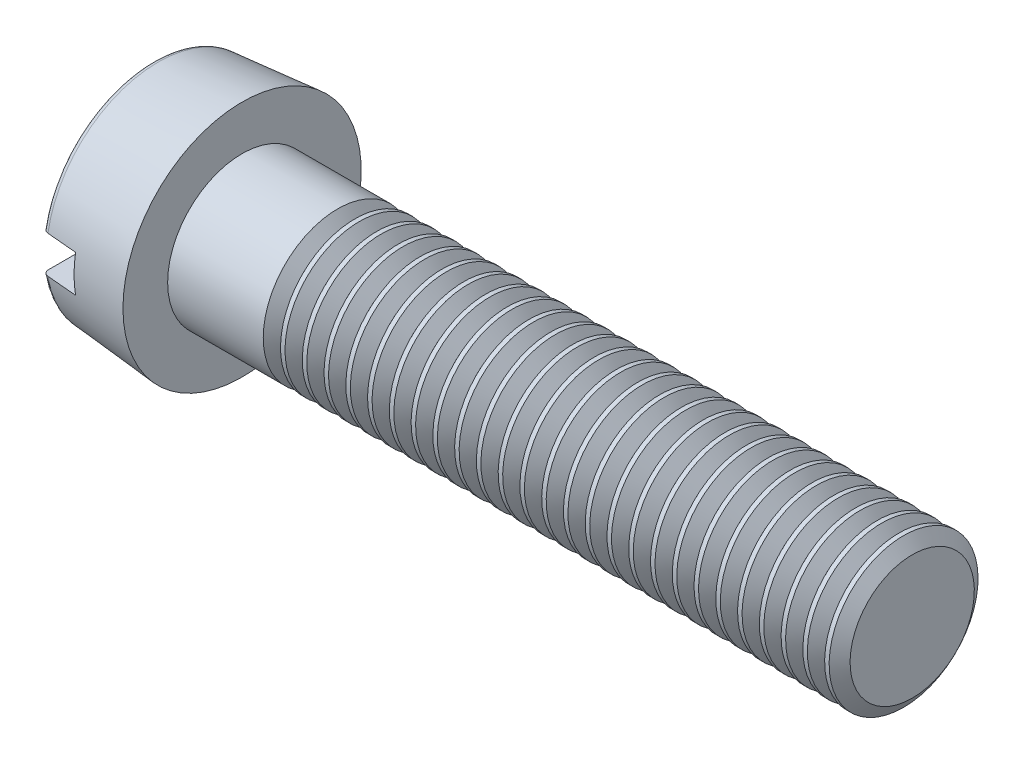
SolidWorks part; units mm, degrees
ref_plane "Plane1" through (0, 0, 0) normal (0, 0, 1) x (1, 0, 0)
ref_plane "Plane2" through (0, 0, 0) normal (0, 1, 0) x (1, 0, 0)
ref_plane "Plane3" through (0, 0, 0) normal (1, 0, 0) x (0, 0, -1)
sketch "BodySke" plane through (0, 0, 0) normal (0, 0, 1) x (1, 0, 0)
  line L0 (6, 5) -> (6, 8)
  line L1 (0, 0) -> (0, 7.4751)
  line L2 (-25.4, 0) -> (127, 0) construction
  line L3 (51, 0) -> (0, 0)
  line L4 (6, 5) -> (51, 5)
  line L5 (51, 5) -> (51, 0)
  line L6 (0, 7.4751) -> (6, 8)
  line L9 (7.5, 6.5875) -> (7.5, -2.9375) construction
  line L10 (13, 6.35) -> (13, -3.175) construction
  dimension "Length" = 45
  dimension "Head_ht" = 6
  dimension "Advance" = 1.5
  dimension "Thread_nom" = 38
  dimension "Head_dia" = 16
  dimension "Head_side_angle" = 5
  dimension "Diameter" = 10
revolve "Base-Revolve" add sketch "BodySke"
cosmetic thread "ThreadCosmetic" [suppressed]
fillet "Fillet1" [suppressed] radius 0.4
fillet "Fillet2" radius 0.4 1 edges at (0, 0, 7.4751)
sketch "Sketch2" plane through (0, 0, 0) normal (1, 0, 0) x (0, 0, -1)
  line L0 (8, -1.25) -> (-8, -1.25)
  line L1 (8, -1.25) -> (8, 1.25)
  line L2 (-8, 1.25) -> (8, 1.25)
  line L3 (-8, 1.25) -> (-8, -1.25)
  dimension "D1" = 16
  dimension "Slot_width" = 2.5
  dimension "D2" = 8
  dimension "D3" = 1.25
extrude "Slot" cut sketch "Sketch2" along normal blind 2.4
sketch "ThdSchSke" plane through (0, 0, 0) normal (0, 0, 1) x (1, 0, 0)
  line L0 (13, -4.172) -> (12.4202, -5)
  line L1 (13, -4.172) -> (13.5798, -5)
  line L2 (13.5798, -5) -> (13.5798, -6.25)
  line L3 (-3.175, 0) -> (5.1513, 0) construction
  line L5 (13.5798, -6.25) -> (12.4202, -6.25)
  line L6 (12.4202, -6.25) -> (12.4202, -5)
  dimension "Diameter" = 10
  dimension "SideAngle" = 55
  dimension "VeeAngle" = 70
  dimension "Thread_minor" = 8.344
  dimension "Overcut" = 12.5
  dimension "Start" = 13
revolve "ThreadSchematic" cut sketch "ThdSchSke" angle 360 about L3
pattern_linear "ThdSchPat" count 27 spacing 1.4615 along (1, 0, 0) of "ThreadSchematic"
equation "\"D1@Sketch2\" = \"Head_dia@BodySke\""
equation "\"D2@Sketch2\" = \"D1@Sketch2\" / 2"
equation "\"D3@Sketch2\" = \"Slot_width@Sketch2\" / 2"
equation "\"Thread_length@ThreadCosmetic\" = ((sgn( (\"Length@BodySke\" - \"Advance@BodySke\" * 2.0 ) - \"Thread_nom@BodySke\" )-1)*( (\"Length@BodySke\" - \"Advance@BodySke\"  * 2.0) - \"Thread_nom@BodySke\" ))/-2+ \"Thread_nom@BodySke\""
equation "\"Thread_minor@ThdSchSke\" = \"Thread_minor@ThreadCosmetic\""
equation "\"Diameter@ThdSchSke\" = \"Diameter@BodySke\""
equation "\"Overcut@ThdSchSke\" = \"Diameter@BodySke\" * 1.25"
equation "\"Start@ThdSchSke\" = \"Head_ht@BodySke\" + \"Length@BodySke\" - \"Thread_length@ThreadCosmetic\"  '---Non-countersunk---"
equation "\"Num_threads@ThdSchPat\" = int( \"Thread_length@ThreadCosmetic\" / \"Advance@BodySke\" + 0.999 )  + 1"
equation "\"Advance@ThdSchPat\" = \"Thread_length@ThreadCosmetic\" /  (\"Num_threads@ThdSchPat\" - 1) 'relax it"
